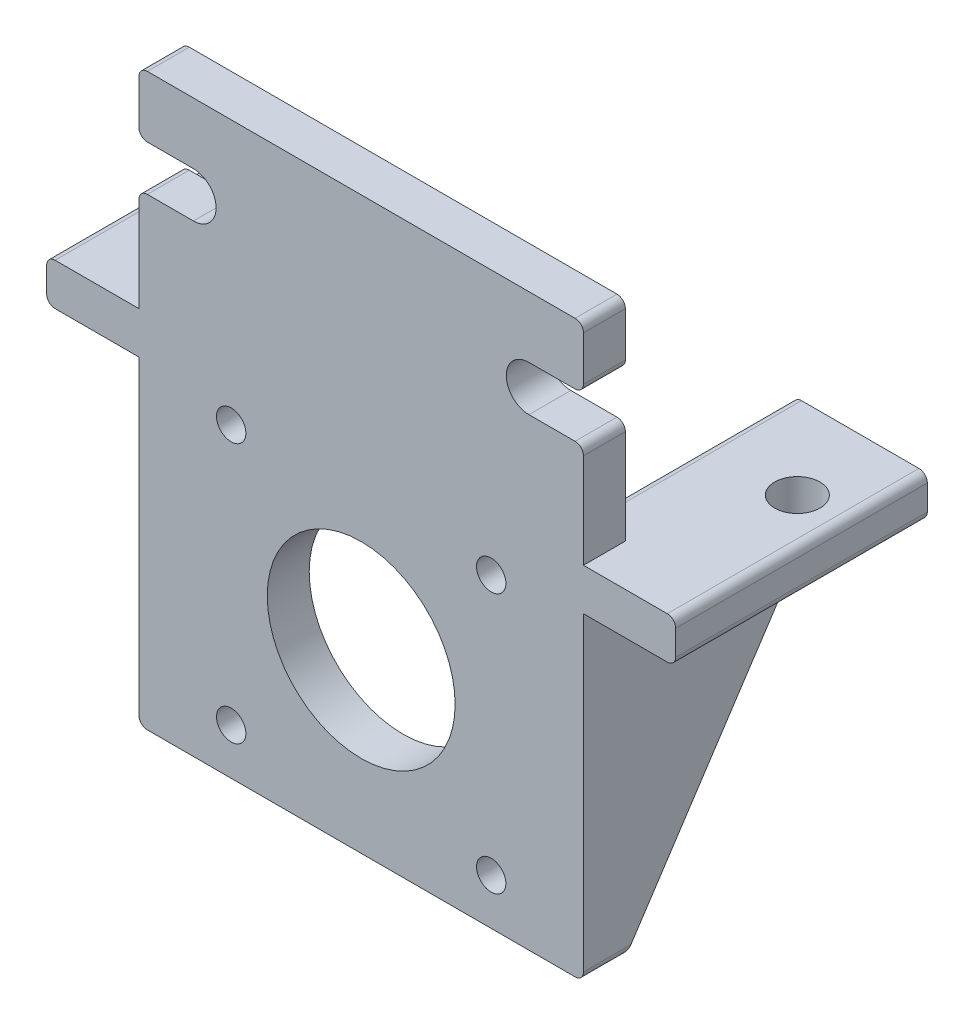
SolidWorks part; units mm, degrees
ref_plane "XY" through (0, 0, 0) normal (0, 0, 1) x (1, 0, 0)
ref_plane "XZ" through (0, 0, 0) normal (0, 1, 0) x (1, 0, 0)
ref_plane "YZ" through (0, 0, 0) normal (1, 0, 0) x (0, 0, -1)
sketch "Sketch1" plane through (0, 0, 0) normal (0, 0, 1) x (1, 0, 0)
  line L0 (0, -13) -> (58.1528, -13) construction
  line L1 (26.5, 34) -> (-26.5, 34)
  line L2 (26.5, 34) -> (26.5, 26.7)
  line L3 (26.5, -34) -> (-26.5, -34)
  line L4 (-26.5, 34) -> (-26.5, 26.7)
  line L5 (26.5, 34) -> (-26.5, -34) construction
  line L6 (26.5, -34) -> (-26.5, 34) construction
  line L7 (0, -13) -> (0, 19.6542) construction
  line L8 (20, 26.7) -> (26.5, 26.7)
  line L9 (20, 21.3) -> (26.5, 21.3)
  line L10 (26.5, 26.7) -> (26.5, 21.3) construction
  line L11 (26.5, 21.3) -> (26.5, -34)
  line L12 (-20, 21.3) -> (-26.5, 21.3)
  line L13 (-20, 26.7) -> (-26.5, 26.7)
  line L14 (-26.5, 26.7) -> (-26.5, 21.3) construction
  line L15 (-26.5, 21.3) -> (-26.5, -34)
  circle A0 centre (0, -13) radius 11.2
  circle A1 centre (15.5, 2.5) radius 1.75
  arc A2 (20, 26.7) -> (20, 21.3) centre (20, 24) ccw
  arc A3 (-20, 26.7) -> (-20, 21.3) centre (-20, 24) cw
  circle A4 centre (15.5, -28.5) radius 1.75
  circle A5 centre (-15.5, 2.5) radius 1.75
  circle A6 centre (-15.5, -28.5) radius 1.75
  point P0 (0, 0)
  dimension "D3" = 5.4
  dimension "D7" = 22.4
  dimension "D10" = 3.5
  dimension "D1" = 53
  dimension "D2" = 68
  dimension "D4" = 20
  dimension "D5" = 24
  dimension "D6" = 13
  dimension "D8" = 2.5
  dimension "D9" = 15.5
extrude "Boss-Extrude1" add sketch "Sketch1" along normal blind 5
sketch "Sketch2" plane through (0, 0, 0) normal (0, 0, -1) x (-1, 0, 0)
  line L0 (26.5, -34) -> (21.5, -34)
  line L1 (26.5, -34) -> (-26.5, -34) construction
  line L2 (21.5, -34) -> (21.5, 9)
  line L3 (21.5, 9) -> (37.5, 9)
  line L4 (37.5, 9) -> (37.5, 4)
  line L5 (37.5, 4) -> (26.5, 4)
  line L6 (26.5, 21.3) -> (26.5, -34) construction
  line L7 (26.5, 4) -> (26.5, -34)
  line L8 (0, 42.48) -> (0, -52.5016) construction
  line L9 (-26.5, 4) -> (-26.5, -34)
  line L10 (-37.5, 4) -> (-26.5, 4)
  line L11 (-37.5, 9) -> (-37.5, 4)
  line L12 (-21.5, 9) -> (-37.5, 9)
  line L13 (-21.5, -34) -> (-21.5, 9)
  line L14 (-26.5, -34) -> (-21.5, -34)
  dimension "D1" = 5
  dimension "D2" = 5
  dimension "D3" = 43
  dimension "D4" = 11
extrude "Boss-Extrude2" add sketch "Sketch2" along normal blind 25
sketch "Sketch3" plane through (-26.5, 0, 0) normal (-1, 0, 0) x (0, 0, 1)
  line L0 (-25, 4) -> (0, -34)
  line L1 (5, -34) -> (-25, -34) construction
  line L2 (0, -34) -> (-25, -34)
  line L3 (-25, -34) -> (-25, 4)
extrude "Cut-Extrude1" cut sketch "Sketch3" against normal through all
sketch "Sketch4" plane through (0, 4, 0) normal (0, -1, 0) x (1, 0, 0)
  line L0 (0, 0) -> (0, -44.5646) construction
  line L1 (26.5, 5) -> (-26.5, 5) construction
  circle A0 centre (32, -15) radius 2.7
  circle A1 centre (-32, -15) radius 2.7
  dimension "D1" = 5.4
  dimension "D2" = 32
  dimension "D3" = 20
extrude "Cut-Extrude2" cut sketch "Sketch4" against normal blind 25
fillet "Fillet1" radius 1 14 edges at (-26.5, 21.3, 2.5) (-26.5, 26.7, 2.5) (26.5, 21.3, 2.5) (26.5, 26.7, 2.5) (26.5, 34, 2.5) (26.5, -34, 2.5) (-26.5, -34, 2.5) (-26.5, 34, 2.5) (-37.5, 4, -12.5) (-37.5, 9, -12.5) (-21.5, 9, -12.5) (21.5, 9, -12.5) (37.5, 4, -12.5) (37.5, 9, -12.5)
sketch "Sketch5" plane through (0, 0, 0) normal (0, 0, 1) x (1, 0, 0)
  line L4 (26.5, 4) -> (36.5, 4)
  line L5 (37.5, 5) -> (37.5, 8)
  line L6 (36.5, 9) -> (26.5, 9)
  line L7 (26.5, 9) -> (26.5, 4)
  line L8 (26.5, 4) -> (36.5, 4)
  line L9 (37.5, 5) -> (37.5, 8)
  line L10 (36.5, 9) -> (26.5, 9)
  line L11 (26.5, 9) -> (26.5, 4)
  arc A2 (36.5, 4) -> (37.5, 5) centre (36.5, 5) ccw
  arc A3 (37.5, 8) -> (36.5, 9) centre (36.5, 8) ccw
  arc A4 (36.5, 4) -> (37.5, 5) centre (36.5, 5) ccw
  arc A5 (37.5, 8) -> (36.5, 9) centre (36.5, 8) ccw
  dimension "D1" = 0
extrude "Boss-Extrude3" add sketch "Sketch5" along normal up to surface (5 mm away) up to face at (-17.25, 2.5, 5)
sketch "Sketch6" plane through (0, 0, 0) normal (0, 0, 1) x (1, 0, 0)
  line L4 (-37.5, 8) -> (-37.5, 5)
  line L5 (-36.5, 4) -> (-26.5, 4)
  line L6 (-26.5, 4) -> (-26.5, 9)
  line L7 (-26.5, 9) -> (-36.5, 9)
  line L8 (-37.5, 8) -> (-37.5, 5)
  line L9 (-36.5, 4) -> (-26.5, 4)
  line L10 (-26.5, 4) -> (-26.5, 9)
  line L11 (-26.5, 9) -> (-36.5, 9)
  arc A2 (-37.5, 5) -> (-36.5, 4) centre (-36.5, 5) ccw
  arc A3 (-36.5, 9) -> (-37.5, 8) centre (-36.5, 8) ccw
  arc A4 (-37.5, 5) -> (-36.5, 4) centre (-36.5, 5) ccw
  arc A5 (-36.5, 9) -> (-37.5, 8) centre (-36.5, 8) ccw
  dimension "D1" = 0
extrude "Boss-Extrude4" add sketch "Sketch6" along normal up to surface (5 mm away) up to face at (-17.25, 2.5, 5)
